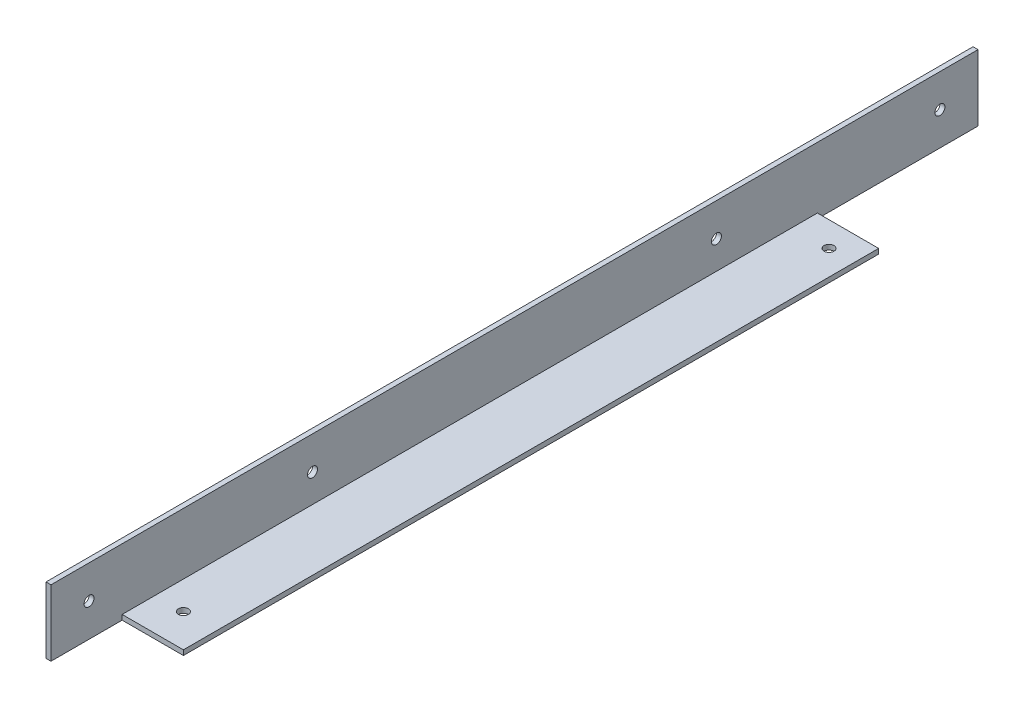
SolidWorks part; units mm, degrees
ref_plane "Plan de face" through (0, 0, 0) normal (0, 0, 1) x (1, 0, 0)
ref_plane "Plan de dessus" through (0, 0, 0) normal (0, 1, 0) x (1, 0, 0)
ref_plane "Plan de droite" through (0, 0, 0) normal (1, 0, 0) x (0, 0, -1)
sketch "Esquisse1" plane through (0, 0, 0) normal (0, 0, 1) x (1, 0, 0)
  line L0 (0, 0) -> (20, 0)
  line L1 (20, 0) -> (20, 1.5)
  line L2 (20, 1.5) -> (1.5, 1.5)
  line L3 (1.5, 1.5) -> (1.5, 20)
  line L4 (1.5, 20) -> (0, 20)
  line L5 (0, 20) -> (0, 0)
  dimension "D1" = 1.5
  dimension "D2" = 1.5
  dimension "D3" = 20
  dimension "D4" = 20
extrude "Extrusion1" add sketch "Esquisse1" along normal blind 280
sketch "Esquisse2" plane through (0, 1.5, 0) normal (0, 1, 0) x (1, 0, 0)
  line L0 (20, -280) -> (20, 0) construction
  line L1 (20, 0) -> (1.5, 0) construction
  line L2 (20, -280) -> (1.5, -280) construction
  circle A0 centre (12.5, -56) radius 1.5
  circle A1 centre (10, -248.5) radius 1.5
  point P8 (10.75, -280)
  dimension "D1" = 7.5
  dimension "D2" = 56
  dimension "D5" = 31.5
  dimension "D6" = 10
extrude "Extrusion2" cut sketch "Esquisse2" against normal through all
sketch "Esquisse3" plane through (0, 0, 0) normal (-1, 0, 0) x (0, 0, 1)
  line L0 (268.5, 10) -> (11.5, 10) construction
  line L1 (280, 20) -> (280, 0) construction
  line L2 (0, 20) -> (0, 0) construction
  line L3 (280, 20) -> (0, 20) construction
  circle A0 centre (268.5, 10) radius 1.5
  circle A1 centre (11.5, 10) radius 1.5
  circle A2 centre (79, 10) radius 1.5
  circle A3 centre (201, 10) radius 1.5
  point P10 (0, 10)
  dimension "D1" = 11.5
  dimension "D2" = 79
  dimension "D3" = 11.5
  dimension "D4" = 79
  dimension "D5" = 10
extrude "Extrusion3" cut sketch "Esquisse3" against normal blind 10
sketch "Esquisse4" plane through (0, 0, 0) normal (0, -1, 0) x (1, 0, 0)
  line L1 (20, 0) -> (1.5, 0)
  line L2 (20, 0) -> (20, 48.5)
  line L3 (20, 48.5) -> (1.5, 48.5)
  line L4 (1.5, 0) -> (1.5, 48.5)
  line L5 (20, 280) -> (1.5, 280)
  line L6 (20, 280) -> (20, 258.5)
  line L7 (20, 258.5) -> (1.5, 258.5)
  line L8 (1.5, 280) -> (1.5, 258.5)
  dimension "D1" = 18.5
  dimension "D2" = 21.5
  dimension "D3" = 18.5
  dimension "D4" = 48.5
extrude "Extrusion4" cut sketch "Esquisse4" against normal blind 1.5
